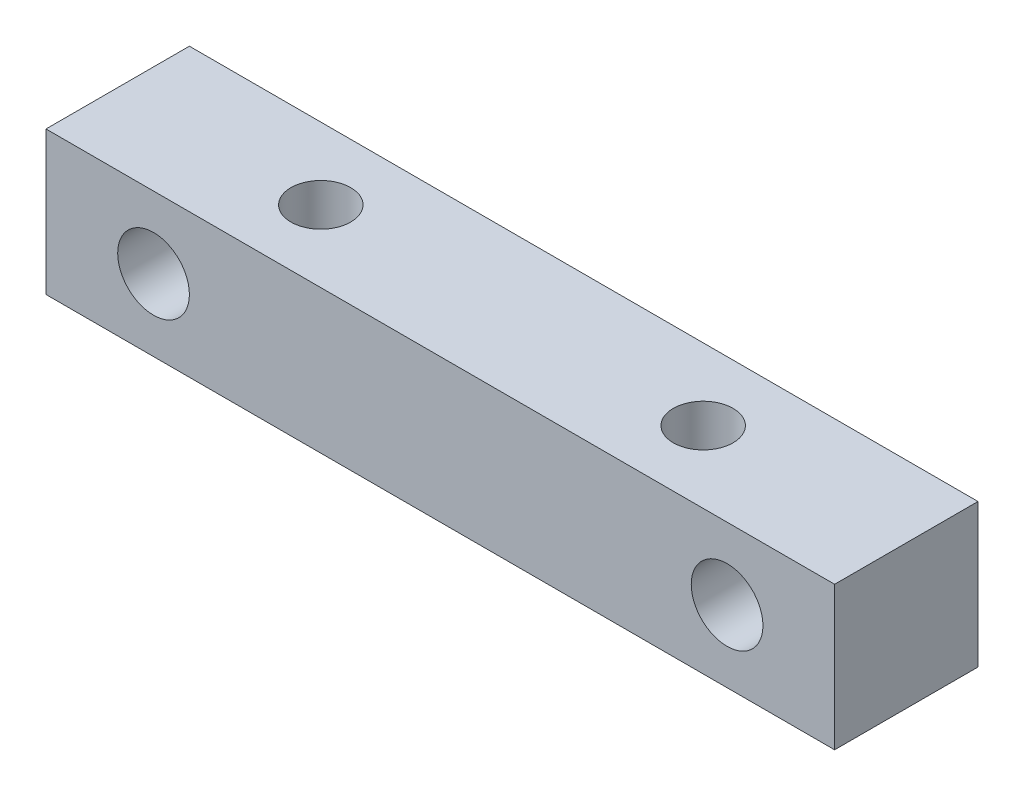
SolidWorks part; units mm, degrees
material "6061-T4 (SS)"
ref_plane "前视基准面" through (0, 0, 0) normal (0, 0, 1) x (1, 0, 0)
ref_plane "上视基准面" through (0, 0, 0) normal (0, 1, 0) x (1, 0, 0)
ref_plane "右视基准面" through (0, 0, 0) normal (1, 0, 0) x (0, 0, -1)
other "Configuration Table"
sketch "草图1" plane through (0, 0, 0) normal (0, 0, 1) x (1, 0, 0)
  line L1 (-22.5, -15) -> (22.5, -15)
  line L2 (-22.5, -15) -> (-22.5, 15)
  line L3 (-22.5, 15) -> (22.5, 15)
  line L4 (22.5, -15) -> (22.5, 15)
  line L5 (-22.5, -15) -> (22.5, 15) construction
  line L6 (-22.5, 15) -> (22.5, -15) construction
  point P0 (0, 0)
  dimension "D1" = 45
  dimension "D2" = 30
extrude "拉伸-薄壁1" add sketch "草图1" along normal blind 6 thin
sketch "草图2" plane through (-26.5, 0, 0) normal (-1, 0, 0) x (0, 0, 1)
  line L0 (3.5, 9) -> (3.5, -9) construction
  line L1 (0, 0) -> (3.5, 0) construction
  line L2 (0, 19) -> (0, -19) construction
  line L3 (6, 19) -> (6, -19) construction
  circle A0 centre (3.5, 9) radius 1.5
  circle A1 centre (3.5, -9) radius 1.5
  dimension "D2" = 3
  dimension "D1" = 18
  dimension "D3" = 2.5
extrude "切除-拉伸1" cut sketch "草图2" against normal blind 59
sketch "草图3" [suppressed] plane through (0, 0, 6) normal (0, 0, 1) x (1, 0, 0)
  circle A0 centre (22.5, 15) radius 1
  circle A1 centre (22.5, -15) radius 1
  circle A2 centre (-22.5, -15) radius 1
  circle A3 centre (-22.5, 15) radius 1
  dimension "D1" = 2
sketch "草图4" plane through (0, 0, 0) normal (0, 0, -1) x (-1, 0, 0)
  line L0 (26.5, 19) -> (26.5, -19) construction
  line L1 (-26.5, -19) -> (26.5, -19)
  line L2 (-26.5, -19) -> (-26.5, -21)
  line L3 (-26.5, -21) -> (26.5, -21)
  line L4 (26.5, -19) -> (26.5, -21)
  dimension "D1" = 2
extrude "凸台-拉伸1" add sketch "草图4" against normal blind 6
sketch "草图5" plane through (0, 0, 0) normal (0, 0, -1) x (-1, 0, 0)
  line L0 (-12, -18) -> (12, -18) construction
  line L1 (0, 0) -> (0, -18) construction
  line L2 (-26.5, -21) -> (26.5, -21) construction
  circle A0 centre (12, -18) radius 1.5
  circle A1 centre (-12, -18) radius 1.5
  dimension "D3" = 3
  dimension "D1" = 24
  dimension "D2" = 3
extrude "切除-拉伸3" cut sketch "草图5" against normal blind 59
sketch "草图6" plane through (0, 0, 6) normal (0, 0, 1) x (1, 0, 0)
  line L0 (-12, -18) -> (12, -18) construction
  line L1 (-12, -15) -> (12, -15)
  line L2 (-12, -21) -> (12, -21)
  line L3 (-22.5, -15) -> (22.5, -15) construction
  arc A0 (-12, -15) -> (-12, -21) centre (-12, -18) ccw
  arc A1 (12, -21) -> (12, -15) centre (12, -18) ccw
  circle A2 centre (12, -18) radius 1.5 construction
  circle A3 centre (-12, -18) radius 1.5 construction
  circle A4 centre (12, -18) radius 1.5
  circle A5 centre (-12, -18) radius 1.5
  point P4 (0, -18)
sketch "草图11" plane through (0, 0, 6) normal (0, 0, 1) x (1, 0, 0)
  line L0 (26.5, -21) -> (26.5, 19) construction
  line L1 (-26.5, 19) -> (26.5, 19)
  line L2 (-26.5, 19) -> (-26.5, 15)
  line L3 (-26.5, 15) -> (26.5, 15)
  line L4 (26.5, 19) -> (26.5, 15)
  line L5 (22.5, 15) -> (-22.5, 15) construction
extrude "切除-拉伸5" cut sketch "草图11" against normal blind 10
sketch "草图12" plane through (0, 0, 6) normal (0, 0, 1) x (1, 0, 0)
  line L0 (26.5, -21) -> (26.5, 15) construction
  line L1 (-26.5, 15) -> (26.5, 15)
  line L2 (-26.5, 15) -> (-26.5, -15)
  line L3 (-26.5, -15) -> (26.5, -15)
  line L4 (26.5, 15) -> (26.5, -15)
  line L5 (-22.5, -15) -> (22.5, -15) construction
extrude "切除-拉伸6" cut sketch "草图12" against normal blind 10
sketch "草图13" plane through (0, -21, 0) normal (0, -1, 0) x (1, 0, 0)
  line L0 (-8, 3) -> (8, 3) construction
  line L1 (0, 3) -> (0, 0) construction
  circle A0 centre (8, 3) radius 1.25
  circle A1 centre (-8, 3) radius 1.25
  dimension "D3" = 2.5
  dimension "D1" = 3
  dimension "D2" = 16
extrude "切除-拉伸7" cut sketch "草图13" against normal blind 10
sketch "草图14" plane through (0, 0, 0) normal (0, 0, -1) x (-1, 0, 0)
  line L0 (-26.5, -21) -> (26.5, -21) construction
  line L1 (26.5, -15) -> (16.5, -15)
  line L2 (26.5, -15) -> (26.5, -21)
  line L3 (26.5, -21) -> (16.5, -21)
  line L4 (16.5, -15) -> (16.5, -21)
  line L5 (0, -15) -> (0, -0.2329) construction
  line L6 (26.5, -15) -> (-26.5, -15) construction
  line L7 (-16.5, -15) -> (-16.5, -21)
  line L8 (-26.5, -21) -> (-16.5, -21)
  line L9 (-26.5, -15) -> (-26.5, -21)
  line L10 (-26.5, -15) -> (-16.5, -15)
  dimension "D1" = 10
extrude "切除-拉伸8" cut sketch "草图14" against normal blind 10
